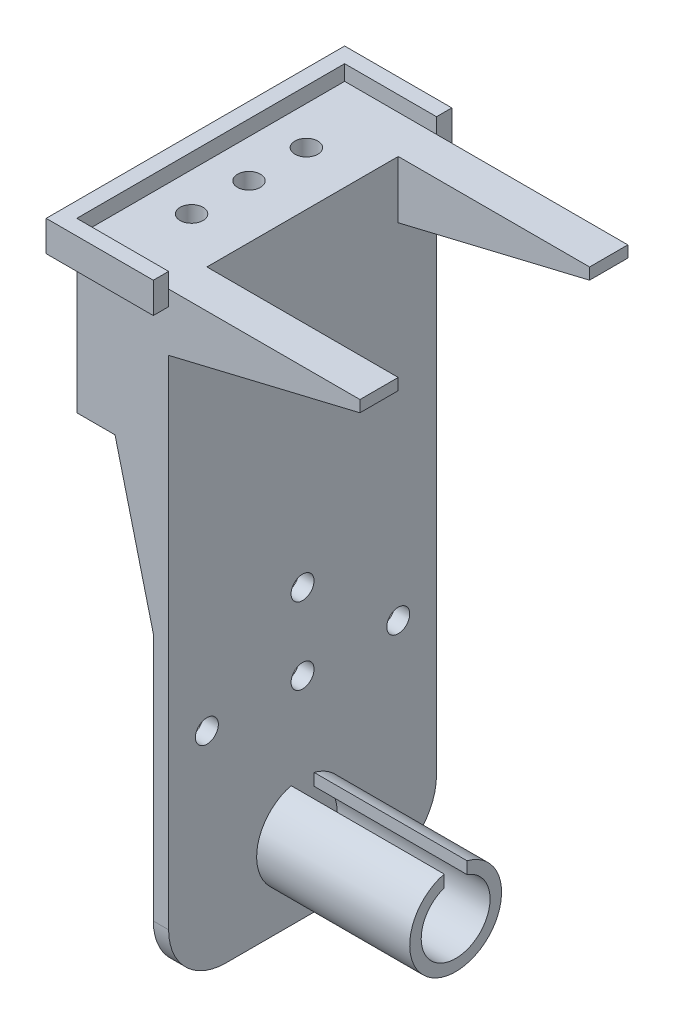
SolidWorks part; units mm, degrees
ref_plane "Alzado" through (0, 0, 0) normal (0, 0, 1) x (1, 0, 0)
ref_plane "Planta" through (0, 0, 0) normal (0, 1, 0) x (1, 0, 0)
ref_plane "Vista lateral" through (0, 0, 0) normal (1, 0, 0) x (0, 0, -1)
sketch "Croquis1" plane through (0, 0, 0) normal (1, 0, 0) x (0, 0, -1)
  line L1 (3, 9) -> (3, 11.619)
  line L2 (-3, 9) -> (-3, 11.619)
  line L3 (-3, 9) -> (-3, 8.4853)
  line L4 (3, 9) -> (3, 8.4853)
  arc A0 (-3, 8.4853) -> (3, 8.4853) centre (0, 0) ccw
  arc A1 (-3, 11.619) -> (3, 11.619) centre (0, 0) ccw
  point P7 (0, 9)
  dimension "D1" = 18
  dimension "D2" = 24
  dimension "D3" = 6
extrude "Saliente-Extruir1" add sketch "Croquis1" along normal blind 40
sketch "Croquis2" plane through (0, 0, 0) normal (-1, 0, 0) x (0, 0, 1)
  line L1 (-35, 0) -> (-35, 140)
  line L2 (-35, 140) -> (35, 140)
  line L3 (35, 140) -> (35, 0)
  line L4 (-35, 0) -> (-35, -20)
  line L5 (-35, -20) -> (35, -20)
  line L6 (35, -20) -> (35, 0)
  point P5 (0, 0)
  dimension "D1" = 70
  dimension "D2" = 140
  dimension "D3" = 20
extrude "Saliente-Extruir2" add sketch "Croquis2" along normal blind 4
sketch "Croquis3" plane through (0, 0, 0) normal (1, 0, 0) x (0, 0, -1)
  circle A0 centre (0, 0) radius 3
  dimension "D1" = 6
extrude "Cortar-Extruir1" cut sketch "Croquis3" against normal up to surface (4 mm away) up to face at (-4, 60, 0)
sketch "Croquis4" plane through (-4, 0, 0) normal (-1, 0, 0) x (0, 0, 1)
  circle A0 centre (0, 0) radius 6
  dimension "D1" = 12
extrude "Cortar-Extruir2" cut sketch "Croquis4" against normal blind 1
sketch "Croquis6" plane through (0, 140, 0) normal (0, 1, 0) x (1, 0, 0)
  line L0 (-14, 35) -> (-14, 30)
  line L1 (-4, 35) -> (-24, 35)
  line L2 (-4, 35) -> (-4, -35)
  line L3 (-4, -35) -> (-24, -35)
  line L4 (-24, 35) -> (-24, -35)
  line L5 (-14, -35) -> (-14, -30)
  line L6 (-14, 30) -> (-14, -30) construction
  circle A2 centre (-14, 15) radius 3
  circle A3 centre (-14, -15) radius 3
  circle A4 centre (-14, 0) radius 3
  line M9 (-4, 35) -> (-4, -35)
  dimension "D4" = 6
  dimension "D6" = 6
  dimension "D8" = 6
  dimension "D1" = 20
  dimension "D2" = 5
  dimension "D3" = 5
  dimension "D5" = 15
  dimension "D7" = 15
extrude "Saliente-Extruir3" add sketch "Croquis6" against normal blind 40 contours L6 L0 L1 L4 L3 L5 A3 A4 A2 | L0 L6 A2 A4 A3 L5 L3 L1 M9
sketch "Croquis7" plane through (0, 0, 0) normal (0, 0, 1) x (1, 0, 0)
  line L0 (0, 140) -> (50, 140)
  line L1 (50, 137) -> (0, 125)
  line L2 (0, -20) -> (0, 140) construction
  line L3 (0, 140) -> (0, 125)
  line L4 (50, 140) -> (50, 137)
  dimension "D1" = 3
  dimension "D2" = 15
  dimension "D3" = 50
extrude "Saliente-Extruir4" add sketch "Croquis7" along normal blind 10 from offset 25
sketch "Croquis8" plane through (0, 0, 0) normal (0, 0, 1) x (1, 0, 0)
  line L0 (0, 140) -> (50, 140)
  line L1 (50, 140) -> (50, 137)
  line L2 (50, 137) -> (0, 125)
  line L3 (0, 125) -> (0, 140)
extrude "Saliente-Extruir5" add sketch "Croquis8" against normal blind 10 from offset 25 offset against normal yes
sketch "Croquis9" plane through (0, 0, 0) normal (0, 1, 0) x (1, 0, 0)
  line L0 (0, 35) -> (0, 39)
  line L1 (0, -35) -> (0, -39)
  line L2 (0, 35) -> (-24, 35)
  line L6 (-24, -39) -> (0, -39)
  line L7 (-24, -39) -> (-28, -39)
  line L8 (-28, -39) -> (-28, 39)
  line L9 (-28, 39) -> (0, 39)
  line L10 (-24, 35) -> (-24, -35)
  line L11 (0, -35) -> (-24, -35)
  dimension "D3" = 4
  dimension "D4" = 4
  dimension "D5" = 78
extrude "Saliente-Extruir6" add sketch "Croquis9" along normal blind 4 and the other way blind 4 from offset 140
sketch "Croquis16" plane through (0, 0, 0) normal (0, 0, 1) x (1, 0, 0)
  line L0 (-14, 100) -> (-4, 60)
  line L1 (-4, 100) -> (-24, 100) construction
  line L2 (-4, -20) -> (-4, 100) construction
  line L3 (-4, 60) -> (-4, 100)
  line L4 (-4, 100) -> (-14, 100)
  dimension "D1" = 40
  dimension "D2" = 10
extrude "Saliente-Extruir7" add sketch "Croquis16" along normal blind 4 from offset 31
sketch "Croquis17" plane through (0, 0, 0) normal (0, 0, 1) x (1, 0, 0)
  line L0 (-4, 100) -> (-14, 100)
  line L1 (-14, 100) -> (-4, 60)
  line L2 (-4, 60) -> (-4, 100)
extrude "Saliente-Extruir8" add sketch "Croquis17" against normal blind 4 from offset 31 offset against normal yes
sketch "Croquis19" plane through (-4, 0, 0) normal (-1, 0, 0) x (0, 0, 1)
  line L2 (-35, -20) -> (-20, -20)
  line L3 (-35, -20) -> (-35, -5)
  line L6 (35, -20) -> (20, -20)
  line L7 (35, -20) -> (35, -5)
  arc A0 (-35, -5) -> (-20, -20) centre (-20, -5) ccw
  arc A1 (20, -20) -> (35, -5) centre (20, -5) ccw
  dimension "D1" = 15
  dimension "D3" = 15
extrude "Cortar-Extruir3" cut sketch "Croquis19" against normal up to surface (4 mm away) contours L3 A0 L2 | L7 A1 L6 up to face at (0, 92.5, 0)
sketch "Croquis20" plane through (-4, 0, 0) normal (-1, 0, 0) x (0, 0, 1)
  line L0 (-35, 60) -> (-35, 50)
  line L1 (-35, 60) -> (-35, -5) construction
  line L2 (35, -5) -> (35, 60) construction
  line L3 (-35, 50) -> (35, 50)
  line L4 (-35, 50) -> (-35, 20)
  line L5 (-35, 20) -> (35, 20)
  line L6 (35, 50) -> (35, 20)
  line L7 (-35, 35) -> (35, 35) construction
  circle A0 centre (0, 35) radius 3
  circle A1 centre (-25, 35) radius 3
  circle A2 centre (25, 35) radius 3
  dimension "D3" = 6
  dimension "D4" = 6
  dimension "D5" = 6
  dimension "D7" = 10
  dimension "D1" = 10
  dimension "D2" = 30
  dimension "D6" = 10
extrude "Cortar-Extruir4" cut sketch "Croquis20" against normal up to surface (4 mm away) contours A1 L7 | L7 A1 | A0 L7 | L7 A0 | A2 L7 | L7 A2 up to face at (0, 0, -3)
sketch "Croquis22" plane through (-4, 0, 0) normal (-1, 0, 0) x (0, 0, 1)
  circle A0 centre (0, 55) radius 3
  circle A1 centre (0, 35) radius 3 construction
  dimension "D2" = 6
  dimension "D1" = 20
extrude "Cortar-Extruir5" cut sketch "Croquis22" against normal up to surface (4 mm away) up to face at (0, 35, -28)
